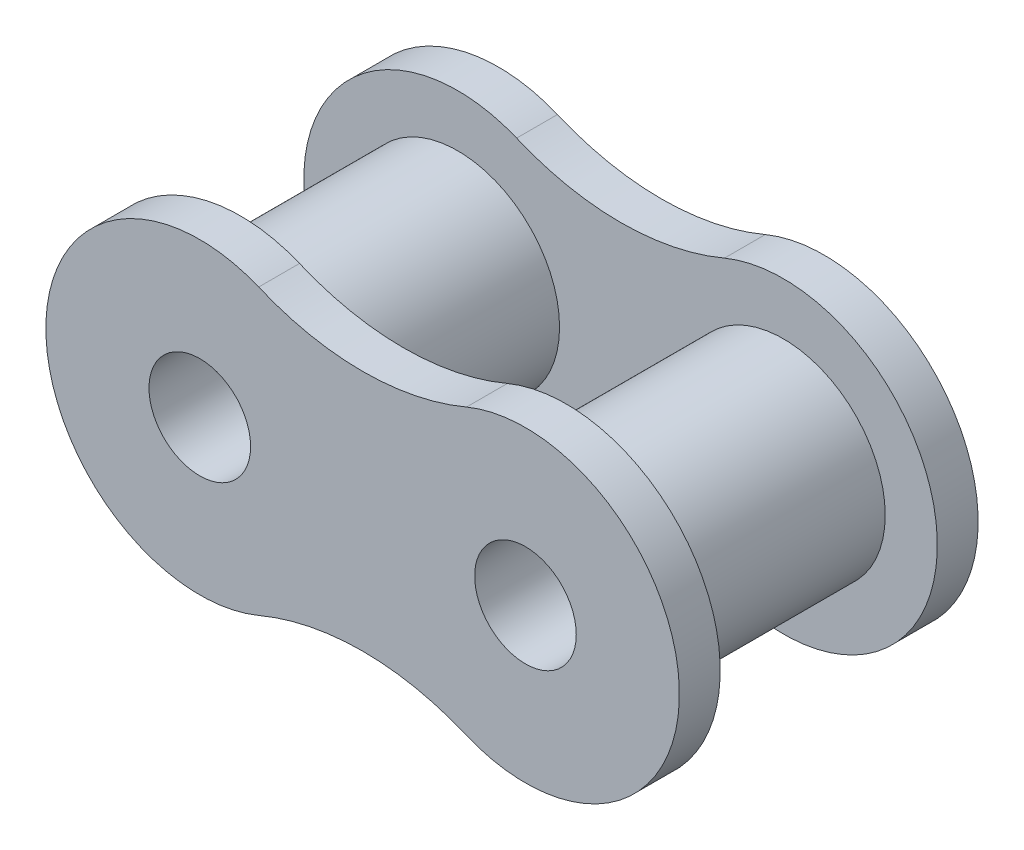
SolidWorks part; units mm, degrees
material "AISI 1020"
ref_plane "Front Plane" through (0, 0, 0) normal (0, 0, 1) x (1, 0, 0)
ref_plane "Top Plane" through (0, 0, 0) normal (0, 1, 0) x (1, 0, 0)
ref_plane "Right Plane" through (0, 0, 0) normal (1, 0, 0) x (0, 0, -1)
sketch "Sketch1" plane through (0, 0, 0) normal (0, 0, 1) x (1, 0, 0)
  line L0 (0, 0) -> (-9.525, 0) construction
  line L1 (0, 0) -> (9.525, 0) construction
  line L2 (-9.525, 9.0043) -> (-0.5207, 0)
  line L3 (-5.0229, 4.5021) -> (-3.158, 6.367)
  line L4 (-9.525, 9.0043) -> (9.525, 9.0043)
  line L5 (-3.158, 6.367) -> (3.158, 6.367)
  line L6 (0, 6.367) -> (0, 9.0043)
  circle A0 centre (9.525, 0) radius 9.0043
  circle A1 centre (-9.525, 0) radius 9.0043
  circle A2 centre (-9.525, 0) radius 2.9718
  circle A3 centre (9.525, 0) radius 2.9718
  arc A4 (-9.525, 9.0043) -> (-3.158, 6.367) centre (-9.525, 0) cw
  arc A5 (3.158, 6.367) -> (9.525, 9.0043) centre (9.525, 0) cw
  arc A6 (-6.0792, 8.3189) -> (6.0792, 8.3189) centre (0, 22.6802) ccw
  arc A7 (-6.0792, -8.3189) -> (6.0792, -8.3189) centre (0, -22.6802) cw
  dimension "D3" = 18.0086
  dimension "D4" = 18.0086
  dimension "D5" = 5.9436
  dimension "D6" = 5.9436
  dimension "D1" = 9.525
  dimension "D2" = 9.525
extrude "Boss-Extrude1" add sketch "Sketch1" along normal blind 2.3876 contours A1 A7 L2 A2 | A6 A1 L2 L3 | A1 A7 A0 L5 | L2 A1 L3 | A6 A1 L5 L6 | A6 L6 L5 A0 | A0 A7 A6 A3
sketch "Sketch2" plane through (0, 0, 2.3876) normal (0, 0, 1) x (1, 0, 0)
  circle A0 centre (-9.525, 0) radius 2.9718
  circle A1 centre (9.525, 0) radius 2.9718
  circle A2 centre (9.525, 0) radius 5.9563
  circle A3 centre (-9.525, 0) radius 5.9563
  circle A4 centre (-9.525, 0) radius 2.9718 construction
  circle A5 centre (9.525, 0) radius 2.9718 construction
  dimension "D1" = 11.9126
  dimension "D2" = 11.9126
extrude "Boss-Extrude2" add sketch "Sketch2" along normal blind 12.7
sketch "Sketch3" plane through (0, 0, 15.0876) normal (0, 0, 1) x (1, 0, 0)
  circle A0 centre (-9.525, 0) radius 2.9718
  circle A1 centre (9.525, 0) radius 2.9718
  circle A2 centre (-9.525, 0) radius 2.9718 construction
  circle A3 centre (9.525, 0) radius 2.9718 construction
  arc A4 (6.0792, -8.3189) -> (6.0792, 8.3189) centre (9.525, 0) ccw
  arc A5 (-6.0792, 8.3189) -> (6.0792, 8.3189) centre (0, 22.6802) ccw
  arc A6 (-6.0792, 8.3189) -> (-6.0792, -8.3189) centre (-9.525, 0) ccw
  arc A7 (6.0792, -8.3189) -> (-6.0792, -8.3189) centre (0, -22.6802) ccw
  arc A8 (6.0792, -8.3189) -> (6.0792, 8.3189) centre (9.525, 0) ccw
  arc A9 (-6.0792, 8.3189) -> (6.0792, 8.3189) centre (0, 22.6802) ccw
  arc A10 (-6.0792, 8.3189) -> (-6.0792, -8.3189) centre (-9.525, 0) ccw
  arc A11 (6.0792, -8.3189) -> (-6.0792, -8.3189) centre (0, -22.6802) ccw
  dimension "D1" = 0
extrude "Boss-Extrude3" add sketch "Sketch3" along normal blind 2.3876
